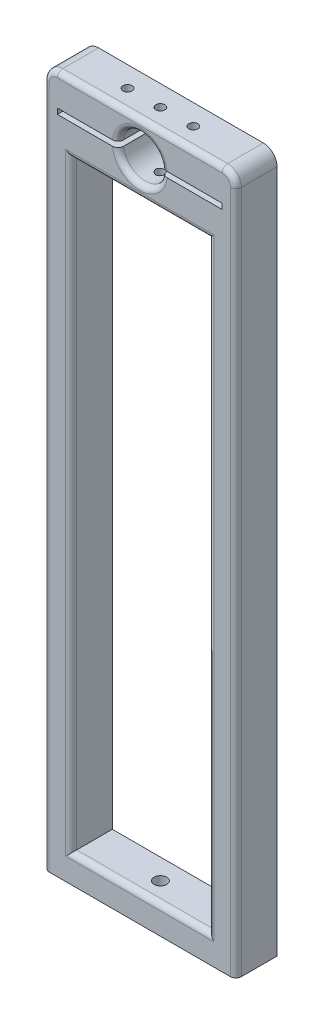
SolidWorks part; units mm, degrees
ref_plane "前视基准面" through (0, 0, 0) normal (0, 0, 1) x (1, 0, 0)
ref_plane "上视基准面" through (0, 0, 0) normal (0, 1, 0) x (1, 0, 0)
ref_plane "右视基准面" through (0, 0, 0) normal (1, 0, 0) x (0, 0, -1)
other "Configuration Table"
sketch "草图1" plane through (0, 0, 0) normal (0, 1, 0) x (1, 0, 0)
  line L1 (-35, -7.5) -> (35, -7.5)
  line L2 (-35, -7.5) -> (-35, 7.5)
  line L3 (-35, 7.5) -> (35, 7.5)
  line L4 (35, -7.5) -> (35, 7.5)
  line L5 (-35, -7.5) -> (35, 7.5) construction
  line L6 (-35, 7.5) -> (35, -7.5) construction
  point P0 (0, 0)
  dimension "D1" = 70
  dimension "D2" = 15
extrude "凸台-拉伸3" add sketch "草图1" along normal blind 254
sketch "草图5" plane through (0, 0, 7.5) normal (0, 0, 1) x (1, 0, 0)
  line L0 (35, 254) -> (35, 0) construction
  line L1 (-25, 229) -> (25, 229)
  line L2 (-25, 229) -> (-25, 10)
  line L3 (-25, 10) -> (25, 10)
  line L4 (25, 229) -> (25, 10)
  line L5 (-35, 254) -> (-35, 0) construction
  line L6 (-35, 254) -> (35, 254) construction
  line L7 (-35, 0) -> (35, 0) construction
  dimension "D1" = 10
  dimension "D2" = 10
  dimension "D3" = 25
  dimension "D4" = 10
extrude "切除-拉伸2" cut sketch "草图5" against normal blind 150
sketch "草图6" plane through (0, 0, 7.5) normal (0, 0, 1) x (1, 0, 0)
  line L0 (0, 254) -> (0, 229)
  line L1 (-35, 254) -> (35, 254) construction
  line L2 (25, 229) -> (-25, 229) construction
  circle A0 centre (0, 241.5) radius 8
  dimension "D1" = 16
extrude "切除-拉伸3" cut sketch "草图6" against normal blind 150 contours A0
fillet "圆角1" radius 2 1 edges at (8, 241.5, 7.5)
fillet "圆角2" radius 5 1 edges at (-35, 254, 0)
fillet "圆角3" radius 5 1 edges at (35, 254, 0)
sketch "草图7" plane through (0, 10, 0) normal (0, 1, 0) x (1, 0, 0)
  circle A0 centre (0, 0) radius 2.3
  dimension "D1" = 4.6
extrude "切除-拉伸4" cut sketch "草图7" against normal blind 150
sketch "草图8" plane through (0, 0, -7.5) normal (0, 0, -1) x (-1, 0, 0)
  line L0 (0, 249.5) -> (0, 233.5)
  line L2 (-30, 240.5) -> (30, 240.5)
  line L3 (-30, 240.5) -> (-30, 242.5)
  line L4 (-30, 242.5) -> (30, 242.5)
  line L5 (30, 240.5) -> (30, 242.5)
  line L6 (-30, 240.5) -> (30, 242.5) construction
  line L7 (-30, 242.5) -> (30, 240.5) construction
  circle A0 centre (0, 241.5) radius 8 construction
  point P5 (0, 241.5)
  dimension "D1" = 30
  dimension "D2" = 2
extrude "切除-拉伸5" cut sketch "草图8" against normal through all contours L2 L5 L4 L3
fillet "圆角4" radius 2 5 edges at (-35, 124.5, 7.5) (0, 254, 7.5) (-33.5355, 252.5355, 7.5) (35, 124.5, 7.5) (33.5355, 252.5355, 7.5)
fillet "圆角7" radius 2 4 edges at (-25, 119.5, 7.5) (0, 10, 7.5) (25, 119.5, 7.5) (0, 229, 7.5)
sketch "草图9" plane through (0, 254, 0) normal (0, 1, 0) x (1, 0, 0)
  line L0 (0, 0) -> (-28.4037, 0)
  line L1 (-28.4037, 0) -> (26.3389, 0)
  circle A0 centre (-12, 0) radius 1.65
  circle A1 centre (12, 0) radius 1.65
  circle A2 centre (0, 0) radius 1.65
  dimension "D2" = 12
  dimension "D3" = 3.3
  dimension "D4" = 3.3
  dimension "D5" = 3.3
  dimension "D1" = 12
extrude "切除-拉伸6" cut sketch "草图9" against normal blind 30 contours A0 | A1 | A2
